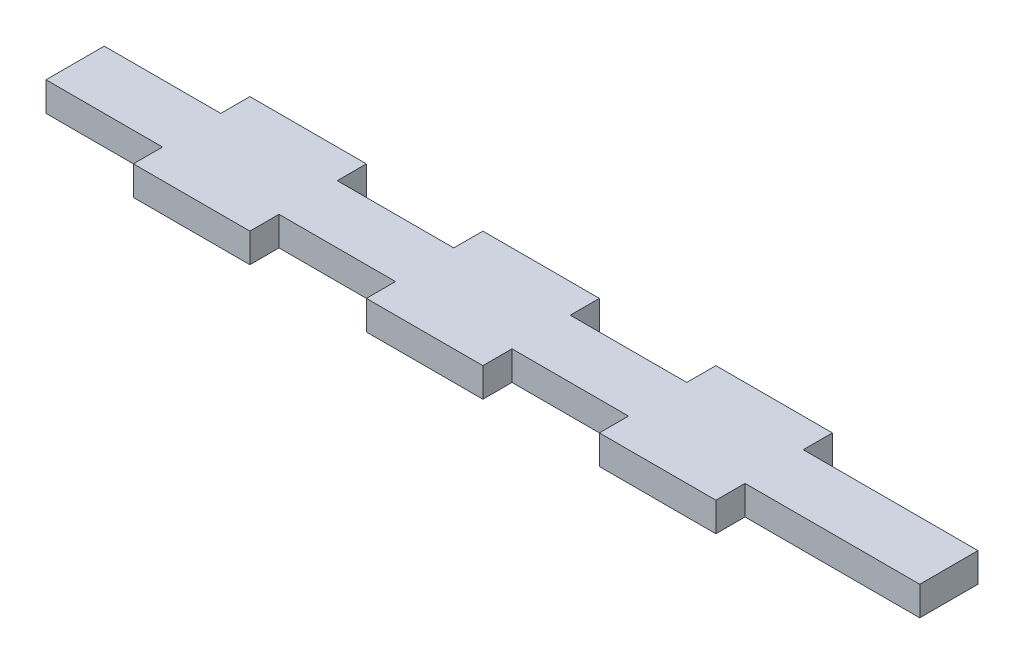
SolidWorks part; units mm, degrees
ref_plane "Front Plane" through (0, 0, 0) normal (0, 0, 1) x (1, 0, 0)
ref_plane "Top Plane" through (0, 0, 0) normal (0, 1, 0) x (1, 0, 0)
ref_plane "Right Plane" through (0, 0, 0) normal (1, 0, 0) x (0, 0, -1)
sketch "Sketch1" plane through (0, 0, 0) normal (0, 0, 1) x (1, 0, 0)
  line L0 (53.5799, -76.2) -> (-104.6669, -76.2) construction
  line L1 (90.6195, 6.35) -> (65.2195, 6.35) construction
  line L2 (90.6195, -158.75) -> (65.2195, -158.75) construction
  line L3 (90.6195, -152.4) -> (90.6195, 0) construction
  line L4 (65.2195, -14.2875) -> (-125.2805, -14.2875)
  line L5 (65.2195, -14.2875) -> (65.2195, -7.9375)
  line L6 (65.2195, -7.9375) -> (-125.2805, -7.9375)
  line L7 (-125.2805, -14.2875) -> (-125.2805, -7.9375)
  dimension "D1" = 6.35
  dimension "D2" = 123.825
  dimension "D3" = 190.5
  dimension "D4" = 25.4
extrude "Boss-Extrude1" add sketch "Sketch1" along normal blind 12.7
sketch "Sketch2" plane through (0, 0, 0) normal (0, 0, -1) x (-1, 0, 0)
  line L0 (-65.2195, -7.9375) -> (125.2805, -7.9375) construction
  line L1 (99.8805, -7.9375) -> (74.4805, -7.9375)
  line L2 (99.8805, -7.9375) -> (99.8805, -14.2875)
  line L3 (99.8805, -14.2875) -> (74.4805, -14.2875)
  line L4 (74.4805, -7.9375) -> (74.4805, -14.2875)
  line L5 (125.2805, -14.2875) -> (-65.2195, -14.2875) construction
  dimension "D1" = 25.4
  dimension "D2" = 25.4
extrude "Boss-Extrude2" add sketch "Sketch2" along normal blind 6.35
pattern_linear "LPattern1" count 3 spacing 50.8 along (1, 0, 0) of "Boss-Extrude2"
sketch "Sketch3" plane through (0, -7.9375, 0) normal (0, 1, 0) x (1, 0, 0)
  line L0 (-125.2805, -6.35) -> (65.2195, -6.35)
  line L1 (-125.2805, -12.7) -> (-125.2805, 0) construction
  line L2 (65.2195, -12.7) -> (65.2195, 0) construction
surface "Surface-Extrude1" sketch "Sketch3" parameters "D1"=25.4
mirror "Mirror1" about plane through (-125.2805, -20.6375, 6.35) normal (0, 0, 1) of "LPattern1", "Boss-Extrude2"
